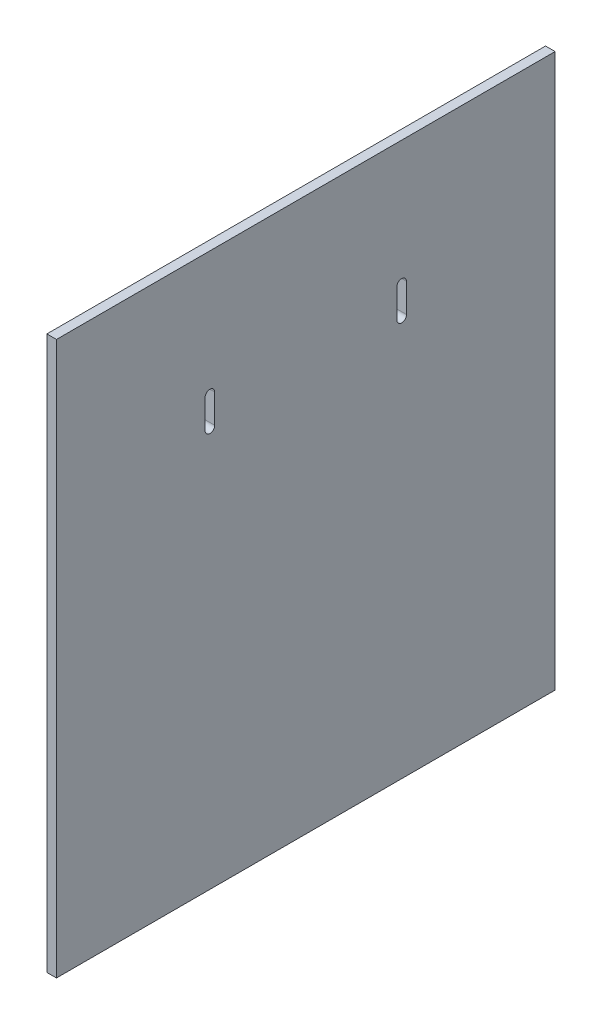
SolidWorks part; units mm, degrees
ref_plane "Front" through (0, 0, 0) normal (0, 0, 1) x (1, 0, 0)
ref_plane "Top" through (0, 0, 0) normal (0, 1, 0) x (1, 0, 0)
ref_plane "Right" through (0, 0, 0) normal (1, 0, 0) x (0, 0, -1)
sketch "Croquis1" plane through (0, 0, 0) normal (1, 0, 0) x (0, 0, -1)
  line L1 (0, 0) -> (156, 0)
  line L2 (0, 0) -> (0, 173)
  line L3 (0, 173) -> (156, 173)
  line L4 (156, 0) -> (156, 173)
  line L5 (0, 0) -> (156, 173) construction
  line L6 (0, 173) -> (156, 0) construction
  point P4 (78, 86.5)
  dimension "D1" = 156
  dimension "D2" = 173
extrude "Saliente-Extruir1" add sketch "Croquis1" along normal blind 3
sketch "Croquis2" plane through (3, 0, 0) normal (1, 0, 0) x (0, 0, -1)
  line L0 (78, 0) -> (78, 125) construction
  line L3 (0, 0) -> (156, 0) construction
  line L4 (78, 125) -> (48, 125) construction
  line L5 (48, 125) -> (48, 134) construction
  line L6 (46.5, 125) -> (46.5, 134)
  line L7 (49.5, 125) -> (49.5, 134)
  line L8 (108, 125) -> (108, 134) construction
  line L9 (109.5, 125) -> (109.5, 134)
  line L10 (106.5, 125) -> (106.5, 134)
  arc A0 (46.5, 125) -> (49.5, 125) centre (48, 125) ccw
  arc A1 (49.5, 134) -> (46.5, 134) centre (48, 134) ccw
  arc A2 (109.5, 125) -> (106.5, 125) centre (108, 125) cw
  arc A3 (106.5, 134) -> (109.5, 134) centre (108, 134) cw
  point P6 (48, 129.5)
  point P11 (49.5, 129.5)
  point P14 (108, 129.5)
  dimension "D1" = 125
  dimension "D2" = 3
  dimension "D3" = 30
  dimension "D4" = 9
extrude "Cortar-Extruir1" cut sketch "Croquis2" against normal through all
